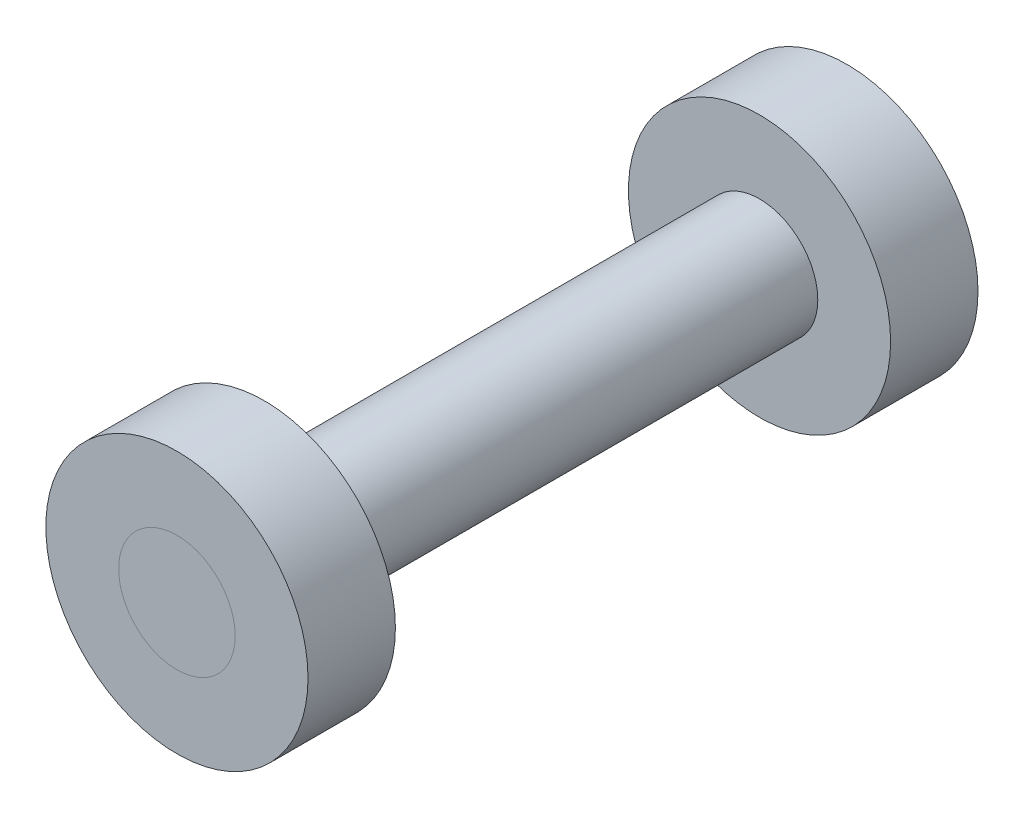
SolidWorks part; units mm, degrees
ref_plane "Alzado" through (0, 0, 0) normal (0, 0, 1) x (1, 0, 0)
ref_plane "Planta" through (0, 0, 0) normal (0, 1, 0) x (1, 0, 0)
ref_plane "Vista lateral" through (0, 0, 0) normal (1, 0, 0) x (0, 0, -1)
sketch "Croquis1" plane through (0, 0, 0) normal (0, 0, 1) x (1, 0, 0)
  circle A0 centre (0, 0) radius 4.5
  dimension "D1" = 9
extrude "Saliente-Extruir1" add sketch "Croquis1" along normal blind 3
sketch "Croquis2" plane through (0, 0, 0) normal (0, 0, 1) x (1, 0, 0)
  circle A0 centre (0, 0) radius 2
  point P2 (0, 0)
  dimension "D1" = 4
extrude "Saliente-Extruir2" add sketch "Croquis2" along normal blind 23
sketch "Croquis4" plane through (0, 0, 0) normal (0, 0, 1) x (1, 0, 0)
  circle A0 centre (0, 0) radius 4.5
  circle A1 centre (0, 0) radius 2
  circle A2 centre (0, 0) radius 2 construction
  point P5 (0, 0)
  dimension "D1" = 9
extrude "Saliente-Extruir3" add sketch "Croquis4" along normal blind 3 from offset 20 separate body
